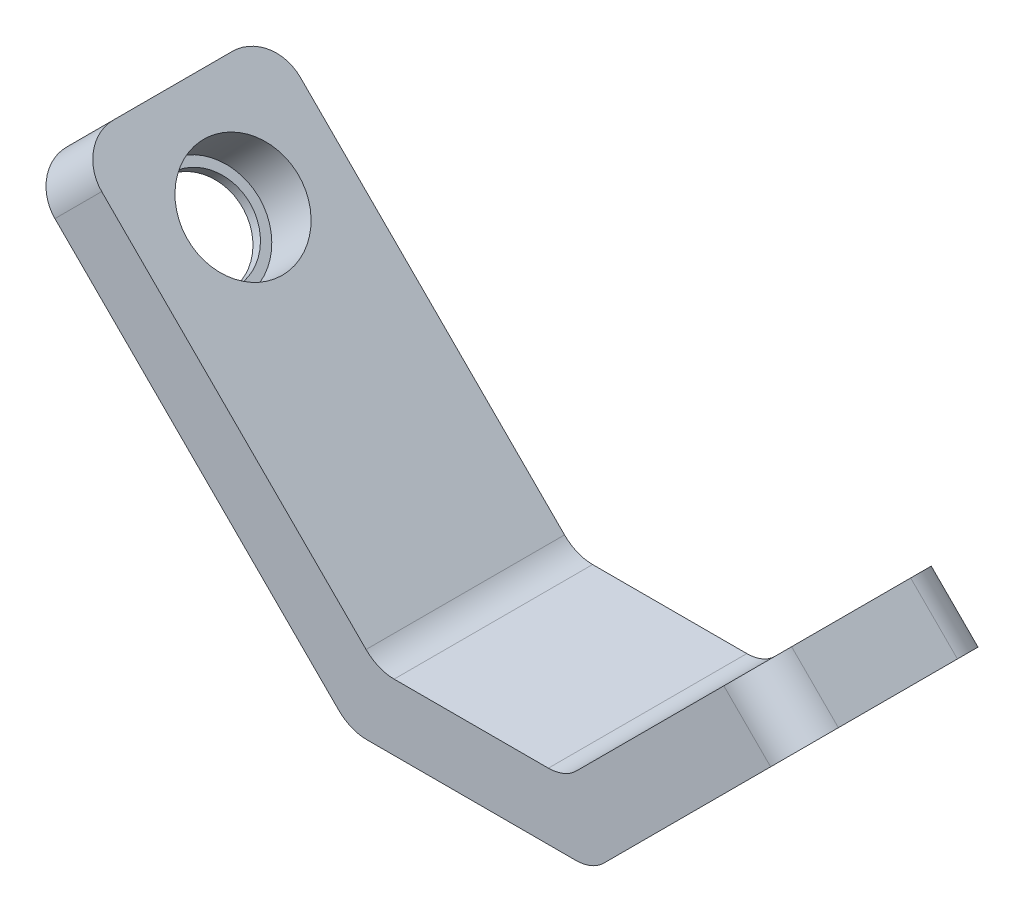
SolidWorks part; units mm, degrees
ref_plane "正面" through (0, 0, 0) normal (0, 0, 1) x (1, 0, 0)
ref_plane "平面" through (0, 0, 0) normal (0, 1, 0) x (1, 0, 0)
ref_plane "右側面" through (0, 0, 0) normal (1, 0, 0) x (0, 0, -1)
sketch "ｽｹｯﾁ1" plane through (0, 0, 0) normal (0, 0, 1) x (1, 0, 0)
  line L0 (0, 0) -> (-24.4454, 24.4454)
  line L1 (-24.4454, 24.4454) -> (-20.9099, 27.981)
  line L2 (-20.9099, 27.981) -> (2.0711, 5)
  line L3 (2.0711, 5) -> (16.2132, 5)
  line L4 (16.2132, 5) -> (30.3553, 19.1421)
  line L5 (30.3553, 19.1421) -> (33.8909, 15.6066)
  line L6 (33.8909, 15.6066) -> (18.2843, 0)
  line L7 (18.2843, 0) -> (0, 0)
  point P6 (23.2843, 12.0711)
  point P10 (-15.6066, 22.6777)
  dimension "D1" = 135
  dimension "D2" = 135
  dimension "D3" = 5
  dimension "D4" = 5
  dimension "D5" = 5
  dimension "D8" = 25
  dimension "D6" = 7.5
  dimension "D7" = 40
  dimension "D9" = 20
extrude "ﾎﾞｽ - 押し出し1" add sketch "ｽｹｯﾁ1" along normal mid plane 15
sketch "ｽｹｯﾁ2" plane through (0, 0, 0) normal (-0.7071, -0.7071, 0) x (0, 0, 1)
  line L1 (7.5, 34.5711) -> (-7.5, 34.5711) construction
  circle A0 centre (0, 27.0711) radius 4.2
  dimension "D1" = 8.4
  dimension "D2" = 7.5
extrude "ｶｯﾄ - 押し出し1" cut sketch "ｽｹｯﾁ2" against normal through all both and the other way through all
sketch "ｽｹｯﾁ3" plane through (9.1421, -9.1421, 0) normal (0.7071, -0.7071, 0) x (0, 0, -1)
  line L1 (-7.5, 35) -> (7.5, 35) construction
  circle A0 centre (0, 27.5) radius 4.2
  point P7 (0, 35)
  dimension "D1" = 8.4
  dimension "D2" = 7.5
extrude "ｶｯﾄ - 押し出し2" cut sketch "ｽｹｯﾁ3" against normal through all both and the other way through all
fillet "ﾌｨﾚｯﾄ1" radius 3 8 edges at (32.1231, 17.3744, -7.5) (32.1231, 17.3744, 7.5) (-22.6777, 26.2132, -7.5) (-22.6777, 26.2132, 7.5) (18.2843, 0, 0) (0, 0, 0) (16.2132, 5, 0) (2.0711, 5, 0)
sketch "ｽｹｯﾁ4" plane through (0, 0, 0) normal (0.7071, 0.7071, 0) x (0, 0, -1)
  circle A0 centre (0, 27.0711) radius 4.2 construction
  circle A1 centre (0, 27.0711) radius 4.2
  circle A2 centre (0, 27.0711) radius 3.5
  dimension "D1" = 7
extrude "ﾎﾞｽ - 押し出し2" add sketch "ｽｹｯﾁ4" along normal blind 0.8
sketch "ｽｹｯﾁ5" plane through (9.1421, -9.1421, 0) normal (-0.7071, 0.7071, 0) x (0, 0, 1)
  circle A0 centre (0, 27.5) radius 4.2 construction
  circle A1 centre (0, 27.5) radius 4.2
  circle A2 centre (0, 27.5) radius 3.5
  dimension "D1" = 7
extrude "ﾎﾞｽ - 押し出し3" add sketch "ｽｹｯﾁ5" along normal blind 0.8
equation "\"D4@ｽｹｯﾁ1\"=\"D3@ｽｹｯﾁ1\""
equation "\"D5@ｽｹｯﾁ1\"=\"D3@ｽｹｯﾁ1\""
